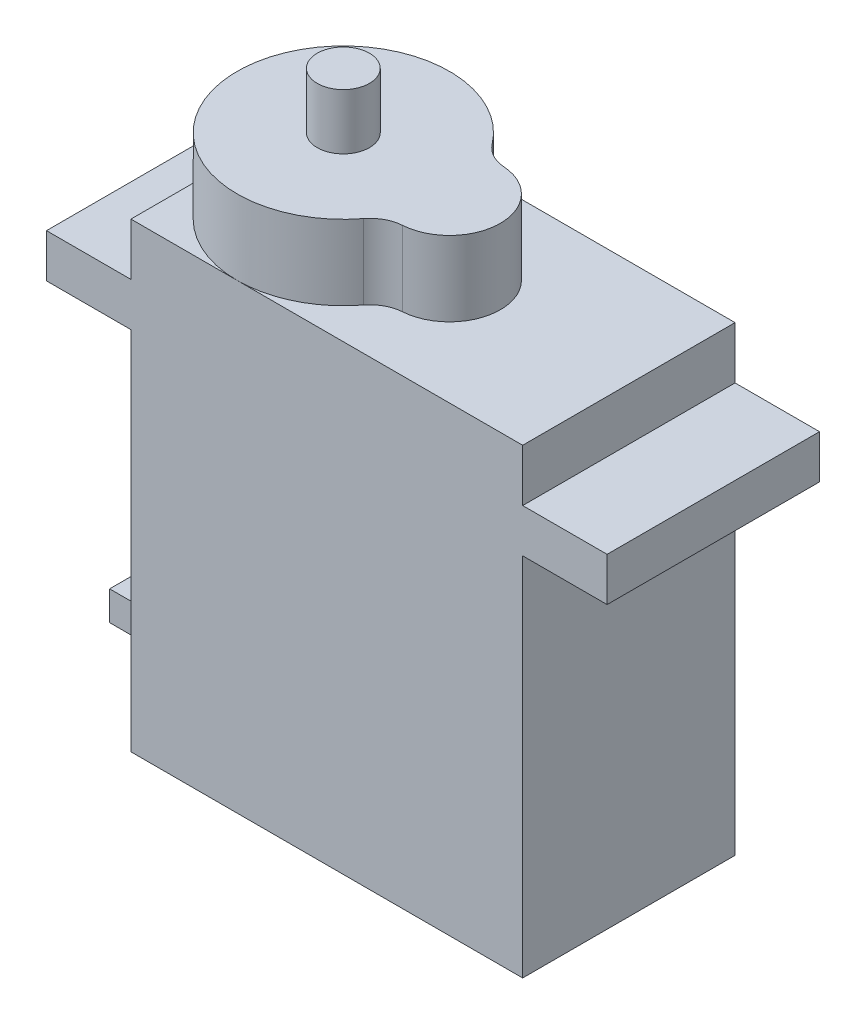
SolidWorks part; units mm, degrees
material "PETG_CF"
ref_plane "Front Plane" through (0, 0, 0) normal (0, 0, 1) x (1, 0, 0)
ref_plane "Top Plane" through (0, 0, 0) normal (0, 1, 0) x (1, 0, 0)
ref_plane "Right Plane" through (0, 0, 0) normal (1, 0, 0) x (0, 0, -1)
sketch "Sketch1" plane through (0, 0, 0) normal (0, 0, 1) x (1, 0, 0)
  line L0 (-11.25, 0) -> (11.25, 0)
  line L1 (11.25, 0) -> (11.25, 21)
  line L2 (11.25, 21) -> (16.1, 21)
  line L3 (16.1, 21) -> (16.1, 23.5)
  line L4 (16.1, 23.5) -> (11.25, 23.5)
  line L5 (11.25, 23.5) -> (11.25, 26.5)
  line L6 (11.25, 26.5) -> (-11.25, 26.5)
  line L7 (0, 26.5) -> (0, 0) construction
  line L8 (-11.25, 23.5) -> (-11.25, 26.5)
  line L9 (-16.1, 23.5) -> (-11.25, 23.5)
  line L10 (-16.1, 21) -> (-16.1, 23.5)
  line L11 (-11.25, 21) -> (-16.1, 21)
  line L12 (-11.25, 0) -> (-11.25, 21)
  dimension "D1" = 22.5
  dimension "D2" = 21
  dimension "D3" = 26.5
  dimension "D4" = 2.5
  dimension "D5" = 32.2
extrude "Boss-Extrude1" add sketch "Sketch1" along normal blind 12.2
sketch "Sketch2" plane through (0, 26.5, 0) normal (0, 1, 0) x (1, 0, 0)
  line L0 (11.25, 0) -> (-11.25, 0) construction
  line L1 (11.25, -12.2) -> (-11.25, -12.2) construction
  line L2 (-11.25, -12.2) -> (-11.25, 0) construction
  arc A0 (-0.2982, -2.4027) -> (-0.2982, -9.7973) centre (-5.15, -6.1) ccw
  arc A1 (1.1534, -9.0143) -> (1.1534, -3.1857) centre (0.95, -6.1) ccw
  arc A2 (-0.2982, -9.7973) -> (1.1534, -9.0143) centre (1.2926, -11.0095) cw
  arc A3 (-0.2982, -2.4027) -> (1.1534, -3.1857) centre (1.2926, -1.1905) ccw
  dimension "D1" = 2
extrude "Boss-Extrude2" add sketch "Sketch2" along normal blind 4.3 contours A0 A2 A1 A3
sketch "Sketch3" plane through (0, 30.8, 0) normal (0, 1, 0) x (1, 0, 0)
  circle A0 centre (-5.15, -6.1) radius 1.5
extrude "Boss-Extrude3" add sketch "Sketch3" along normal blind 3.2
sketch "Sketch4" plane through (-11.25, 0, 0) normal (-1, 0, 0) x (0, 0, 1)
  line L0 (6.1, 0) -> (6.1, 21) construction
  line L1 (12.2, 0) -> (0, 0) construction
  line L2 (12.2, 21) -> (0, 21) construction
  line L4 (3.7771, 2.0366) -> (8.4229, 2.0366)
  line L5 (3.7771, 2.0366) -> (3.7771, 3.719)
  line L6 (3.7771, 3.719) -> (8.4229, 3.719)
  line L7 (8.4229, 2.0366) -> (8.4229, 3.719)
  line L8 (3.7771, 2.0366) -> (8.4229, 3.719) construction
  line L9 (3.7771, 3.719) -> (8.4229, 2.0366) construction
  point P6 (6.1, 2.8778)
extrude "Boss-Extrude4" add sketch "Sketch4" along normal blind 5
